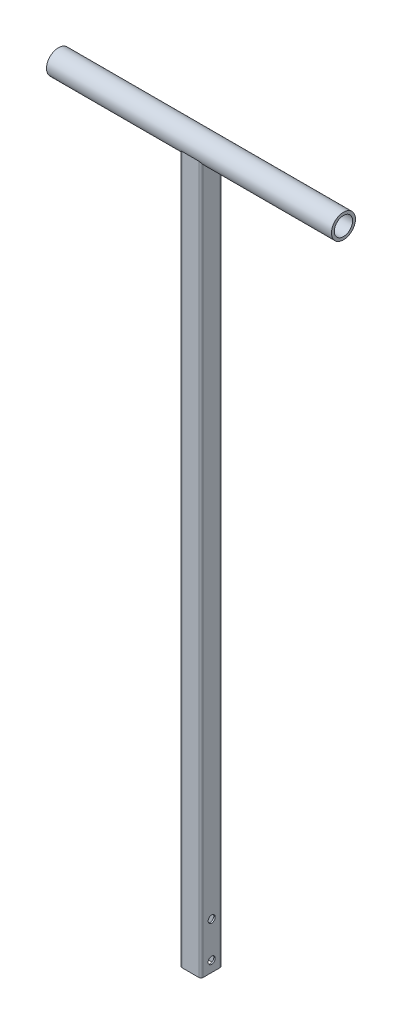
SolidWorks part; units mm, degrees
ref_plane "Plano frontal" through (0, 0, 0) normal (0, 0, 1) x (1, 0, 0)
ref_plane "Plano superior" through (0, 0, 0) normal (0, 1, 0) x (1, 0, 0)
ref_plane "Plano direito" through (0, 0, 0) normal (1, 0, 0) x (0, 0, -1)
sketch "Esboço1" plane through (0, 0, 0) normal (0, 0, 1) x (1, 0, 0)
  line L0 (0, 0) -> (400, 0)
  line L1 (200, 0) -> (200, -1000)
  dimension "D1" = 1000
  dimension "D2" = 400
ref_plane "Plano1" through (200, 0, 0) normal (0, -1, 0) x (1, 0, 0)
other "Square tube - configured 40 X 40 X 4(1)"
ref_plane "Plano2" through (200, 0, 0) normal (0, -1, 0) x (1, 0, 0)
sketch "Sketch12" plane through (200, 0, 0) normal (0, -1, 0) x (1, 0, 0)
  line L0 (-12, -13) -> (12, -13)
  line L1 (-13, -12) -> (-13, 12)
  line L2 (12, 13) -> (-12, 13)
  line L3 (13, 12) -> (13, -12)
  line L4 (-12, -15) -> (12, -15)
  line L5 (-15, -12) -> (-15, 12)
  line L6 (12, 15) -> (-12, 15)
  line L7 (15, 12) -> (15, -12)
  arc A0 (15, 12) -> (12, 15) centre (12, 12) ccw
  arc A1 (12, -15) -> (15, -12) centre (12, -12) ccw
  arc A2 (-15, -12) -> (-12, -15) centre (-12, -12) ccw
  arc A3 (-12, 15) -> (-15, 12) centre (-12, 12) ccw
  arc A4 (-12, 13) -> (-13, 12) centre (-12, 12) ccw
  arc A5 (13, 12) -> (12, 13) centre (12, 12) ccw
  arc A6 (12, -13) -> (13, -12) centre (12, -12) ccw
  arc A7 (-13, -12) -> (-12, -13) centre (-12, -12) ccw
  point P0 (-15, 0)
  point P1 (15, 0)
  point P2 (0, 15)
  point P3 (0, -15)
  point P4 (0, 0)
  point P5 (-15, -15)
  point P6 (15, -15)
  point P7 (15, 15)
  point P8 (-15, 15)
  point P33 (0, 0)
  dimension "D1" = 3
  dimension "Thickness" = 2
  dimension "V_leg" = 30
other "Pipe - configured 33.7 X 4.0(2)"
ref_plane "Plano3" through (0, 0, 0) normal (1, 0, 0) x (0, 1, 0)
sketch "Sketch11" plane through (0, 0, 0) normal (1, 0, 0) x (0, 1, 0)
  circle A0 centre (0, 0) radius 12.85
  circle A1 centre (0, 0) radius 16.85
  point P3 (0, 0)
  dimension "In_dia" = 25.7
  dimension "Out_dia" = 33.7
other "Aparar/Estender1"
sketch "Esboço5" plane through (215, 0, 0) normal (1, 0, 0) x (0, 0, -1)
  line L0 (0, -1000) -> (0, -870) construction
  line L1 (12, -1000) -> (-12, -1000) construction
  circle A0 centre (0, -985) radius 5
  circle A1 centre (0, -935) radius 5
  dimension "D1" = 10
  dimension "D2" = 15
  dimension "D3" = 50
extrude "Corte-extrusão1" cut sketch "Esboço5" against normal through all
